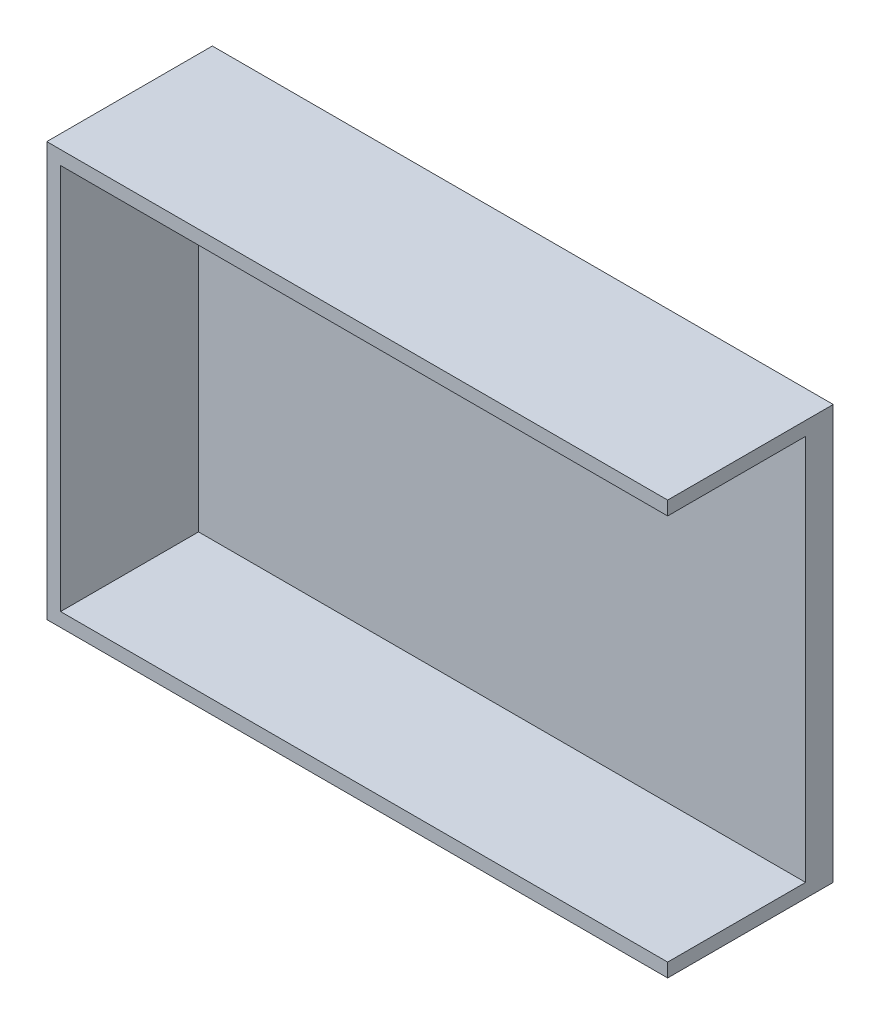
SolidWorks part; units mm, degrees
ref_plane "Front Plane" through (0, 0, 0) normal (0, 0, 1) x (1, 0, 0)
ref_plane "Top Plane" through (0, 0, 0) normal (0, 1, 0) x (1, 0, 0)
ref_plane "Right Plane" through (0, 0, 0) normal (1, 0, 0) x (0, 0, -1)
sketch "Sketch1" plane through (0, 0, 0) normal (0, 0, 1) x (1, 0, 0)
  line L1 (0, 0) -> (45, 0)
  line L2 (0, 0) -> (0, 30)
  line L3 (0, 30) -> (45, 30)
  line L4 (45, 0) -> (45, 30)
  dimension "D1" = 30
  dimension "D2" = 45
extrude "Boss-Extrude1" add sketch "Sketch1" along normal blind 12
sketch "Sketch2" plane through (0, 0, 12) normal (0, 0, 1) x (1, 0, 0)
  line L0 (45, 30) -> (0, 30) construction
  line L1 (1, 29) -> (45, 29)
  line L2 (1, 29) -> (1, 1)
  line L3 (1, 1) -> (45, 1)
  line L4 (45, 29) -> (45, 1)
  line L5 (0, 30) -> (0, 0) construction
  line L6 (0, 0) -> (45, 0) construction
  line L7 (45, 0) -> (45, 30) construction
  dimension "D1" = 1
  dimension "D2" = 1
  dimension "D3" = 1
  dimension "D4" = 0
extrude "Cut-Extrude1" cut sketch "Sketch2" against normal blind 10
